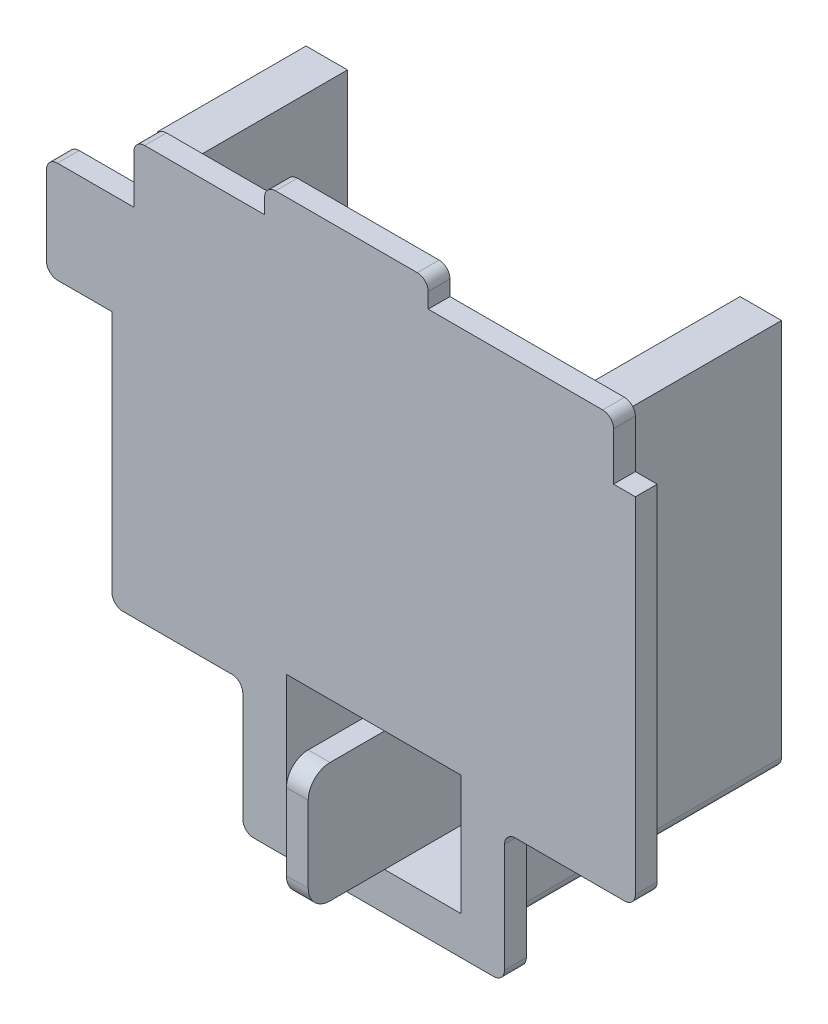
SolidWorks part; units mm, degrees
ref_plane "Front Plane" through (0, 0, 0) normal (0, 0, 1) x (1, 0, 0)
ref_plane "Top Plane" through (0, 0, 0) normal (0, 1, 0) x (1, 0, 0)
ref_plane "Right Plane" through (0, 0, 0) normal (1, 0, 0) x (0, 0, -1)
sketch "Sketch1" plane through (0, 0, 0) normal (0, 0, 1) x (1, 0, 0)
  line L0 (0, 0) -> (12, 0)
  line L1 (12, 0) -> (12, 12)
  line L2 (12, 12) -> (24, 12)
  line L3 (24, 12) -> (24, 44.6)
  line L4 (24, 44.6) -> (22, 44.6)
  line L5 (22, 44.6) -> (22, 50)
  line L6 (22, 50) -> (5, 50)
  line L7 (5, 50) -> (5, 52.4)
  line L8 (5, 52.4) -> (-10, 52.4)
  line L9 (-10, 52.4) -> (-10, 50)
  line L10 (-10, 50) -> (-22, 50)
  line L11 (-22, 50) -> (-22, 44.6)
  line L12 (-22, 44.6) -> (-30, 44.6)
  line L13 (-30, 44.6) -> (-30, 35.3)
  line L14 (-30, 35.3) -> (-24, 35.3)
  line L15 (-24, 35.3) -> (-24, 12)
  line L16 (-24, 12) -> (-12, 12)
  line L17 (-12, 12) -> (-12, 0)
  line L18 (-12, 0) -> (0, 0)
  line L19 (0, 0) -> (0, 35.3) construction
  point P19 (0, 0)
  dimension "D1" = 24
  dimension "D2" = 12
  dimension "D3" = 12
  dimension "D4" = 6
  dimension "D5" = 8
  dimension "D6" = 12
  dimension "D7" = 15
  dimension "D8" = 17
  dimension "D9" = 2
  dimension "D10" = 12
  dimension "D11" = 38
  dimension "D12" = 2.4
  dimension "D13" = 9.3
  dimension "D14" = 5.4
  dimension "D15" = 23.3
extrude "Boss-Extrude1" add sketch "Sketch1" along normal blind 2
fillet "Fillet1" radius 1 12 edges at (-30, 35.3, 1) (-30, 44.6, 1) (-22, 50, 1) (22, 50, 1) (-24, 12, 1) (24, 12, 1) (-12, 0, 1) (12, 0, 1) (12, 12, 1) (-12, 12, 1) (-10, 52.4, 1) (5, 52.4, 1)
sketch "Sketch3" plane through (0, 0, 0) normal (0, 0, -1) x (-1, 0, 0)
  line L0 (-21.8, 49.7) -> (-21.8, 14)
  line L2 (-21.8, 14) -> (-9.8, 14)
  line L3 (-9.8, 14) -> (-9.8, 2.2)
  line L4 (-9.8, 2.2) -> (9.8, 2.2)
  line L5 (9.8, 2.2) -> (9.8, 14)
  line L6 (9.8, 14) -> (21.8, 14)
  line L7 (21.8, 14) -> (21.8, 49.7)
  line L9 (21.8, 49.7) -> (18, 49.7)
  line L10 (18, 49.7) -> (18, 21.8)
  line L11 (18, 21.8) -> (-18, 21.8)
  line L12 (-18, 21.8) -> (-18, 49.7)
  line L13 (-18, 49.7) -> (-21.8, 49.7)
  line L14 (-22, 44.6) -> (-22, 49) construction
  line L15 (11, 0) -> (-11, 0) construction
  line L16 (12, 11) -> (12, 1) construction
  line L17 (-12, 1) -> (-12, 11) construction
  line L18 (23, 12) -> (13, 12) construction
  line L19 (-13, 12) -> (-23, 12) construction
  line L20 (24, 35.3) -> (24, 13) construction
  point P11 (0, 0)
  dimension "D1" = 3.8
  dimension "D2" = 3.8
  dimension "D3" = 43.6
  dimension "D4" = 0.2
  dimension "D5" = 2.2
  dimension "D6" = 2.2
  dimension "D7" = 2.2
  dimension "D8" = 2
  dimension "D9" = 2
  dimension "D10" = 2.2
  dimension "D11" = 35.7
  dimension "D12" = 19.6
extrude "Boss-Extrude2" add sketch "Sketch3" along normal blind 13.6
sketch "Sketch4" plane through (0, 0, 2) normal (0, 0, 1) x (1, 0, 0)
  line L0 (-11, 0) -> (11, 0) construction
  line L1 (8, 3.5) -> (1, 3.5)
  line L2 (8, 3.5) -> (8, 14.5)
  line L3 (8, 14.5) -> (1, 14.5)
  line L4 (1, 3.5) -> (1, 14.5)
  line L5 (-1, 3.5) -> (-8, 3.5)
  line L6 (-1, 3.5) -> (-1, 14.5)
  line L7 (-1, 14.5) -> (-8, 14.5)
  line L8 (-8, 3.5) -> (-8, 14.5)
  line L9 (12, 1) -> (12, 11) construction
  line L10 (-12, 11) -> (-12, 1) construction
  dimension "D1" = 3.5
  dimension "D2" = 4
  dimension "D3" = 11
  dimension "D4" = 7
  dimension "D5" = 4
  dimension "D6" = 3.5
  dimension "D7" = 11
  dimension "D8" = 2
  dimension "D9" = 7
extrude "Cut-Extrude1" cut sketch "Sketch4" against normal blind 11.2
sketch "Sketch5" plane through (0, 0, 2) normal (0, 0, 1) x (1, 0, 0)
  line L1 (1, 3.5) -> (-1, 3.5)
  line L2 (1, 3.5) -> (1, 14.5)
  line L3 (1, 14.5) -> (-1, 14.5)
  line L4 (-1, 3.5) -> (-1, 14.5)
extrude "Boss-Extrude3" add sketch "Sketch5" along normal blind 7
fillet "Fillet2" radius 2 2 edges at (0, 14.5, 9) (0, 3.5, 9)
fillet "Fillet3" radius 1 6 edges at (21.8, 14, -6.8) (9.8, 14, -6.8) (-21.8, 14, -6.8) (-9.8, 14, -6.8) (-9.8, 2.2, -6.8) (9.8, 2.2, -6.8)
